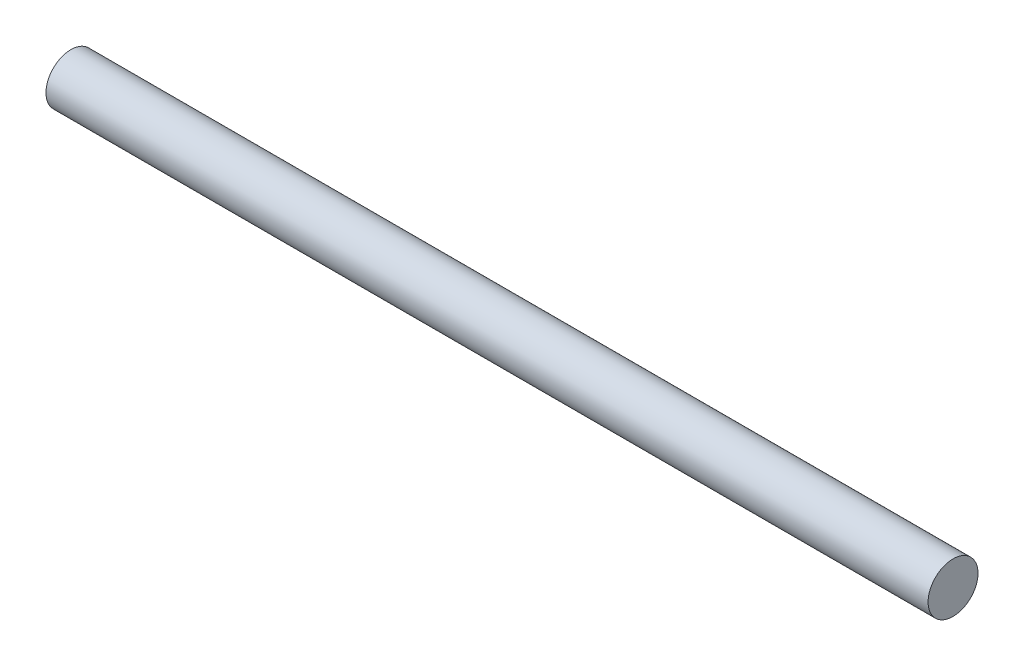
SolidWorks part; units mm, degrees
material "AISI 321 Отожженная нержавеющая сталь (SS)"
ref_plane "Спереди" through (0, 0, 0) normal (0, 0, 1) x (1, 0, 0)
ref_plane "Сверху" through (0, 0, 0) normal (0, 1, 0) x (1, 0, 0)
ref_plane "Справа" through (0, 0, 0) normal (1, 0, 0) x (0, 0, -1)
sketch "Эскиз1" plane through (0, 0, 0) normal (1, 0, 0) x (0, 0, -1)
  circle A0 centre (0, 0) radius 3
  dimension "D1" = 6
extrude "Бобышка-Вытянуть1" add sketch "Эскиз1" along normal mid plane 106
